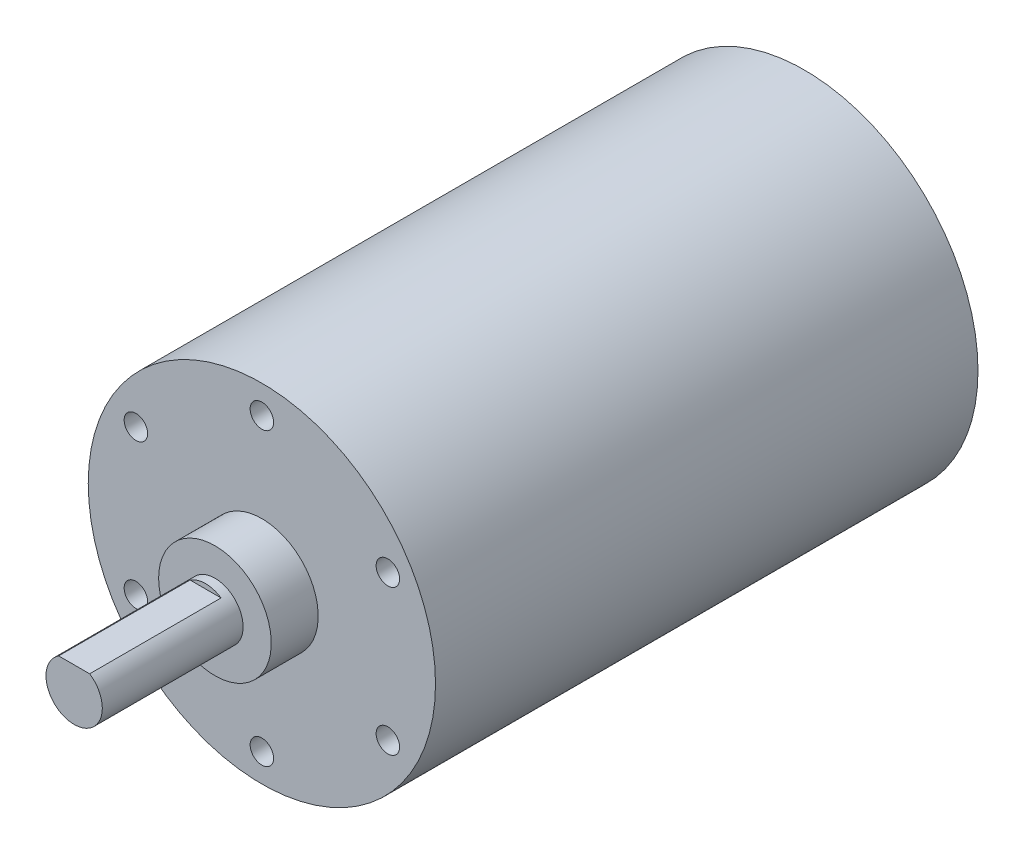
SolidWorks part; units mm, degrees
ref_plane "Front Plane" through (0, 0, 0) normal (0, 0, 1) x (1, 0, 0)
ref_plane "Top Plane" through (0, 0, 0) normal (0, 1, 0) x (1, 0, 0)
ref_plane "Right Plane" through (0, 0, 0) normal (1, 0, 0) x (0, 0, -1)
sketch "Sketch3" plane through (0, 0, 0) normal (0, 0, 1) x (1, 0, 0)
  circle A0 centre (0, 0) radius 18.5
  dimension "D1" = 36.9999
extrude "Boss-Extrude1" add sketch "Sketch3" against normal blind 57.8
sketch "Sketch4" plane through (0, 0, 0) normal (0, 0, 1) x (1, 0, 0)
  circle A0 centre (0, 0) radius 3
  dimension "D1" = 6
extrude "Boss-Extrude2" add sketch "Sketch4" along normal blind 20
sketch "Sketch6" plane through (0, 0, 0) normal (0, 0, 1) x (1, 0, 0)
  circle A0 centre (0, 0) radius 6
  dimension "D1" = 12
extrude "Boss-Extrude3" add sketch "Sketch6" along normal blind 5
sketch "Sketch7" plane through (0, 0, 20) normal (0, 0, 1) x (1, 0, 0)
  line L0 (-1.6528, 2.5036) -> (1.6528, 2.5036)
  line L1 (1.6528, 2.5036) -> (1.6528, 3.0036)
  line L2 (1.6528, 3.0036) -> (-1.6528, 3.0036)
  line L3 (-1.6528, 3.0036) -> (-1.6528, 2.5036)
  circle A0 centre (0, 0) radius 3 construction
  dimension "D1" = 0.5
sketch "Sketch8" plane through (0, 0, 0) normal (0, 0, 1) x (1, 0, 0)
  circle A0 centre (0, 0) radius 15.5
  circle A1 centre (0, 15.5) radius 1.25
  circle A2 centre (13.4234, 7.75) radius 1.25
  circle A3 centre (13.4234, -7.75) radius 1.25
  circle A4 centre (0, -15.5) radius 1.25
  circle A5 centre (-13.4234, -7.75) radius 1.25
  circle A6 centre (-13.4234, 7.75) radius 1.25
  point P17 (0, 0)
  dimension "D1" = 30.9999
  dimension "D2" = 6
extrude "Cut-Extrude3" cut sketch "Sketch8" against normal blind 8.89 contours A3 | A4 | A5 | A2 | A1 | A6
extrude "Cut-Extrude4" cut sketch "Sketch7" against normal blind 14
